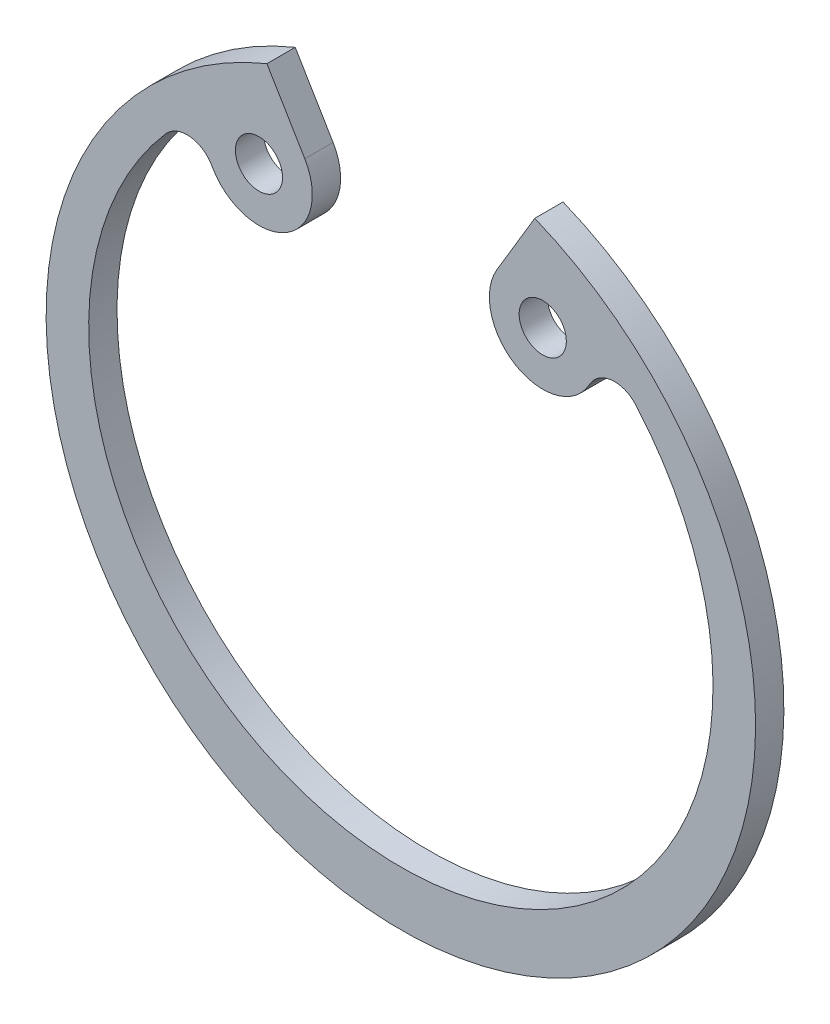
SolidWorks part; units mm, degrees
material "S890"
ref_plane "Front Plane" through (0, 0, 0) normal (0, 0, 1) x (1, 0, 0)
ref_plane "Top Plane" through (0, 0, 0) normal (0, 1, 0) x (1, 0, 0)
ref_plane "Right Plane" through (0, 0, 0) normal (1, 0, 0) x (0, 0, -1)
sketch "Sketch1" plane through (0, 0, 0) normal (0, 0, 1) x (1, 0, 0)
  line L0 (7.0978, 17.4087) -> (5.0915, 14.0476)
  line L1 (9.9485, 11.1484) -> (11.0285, 12.9577)
  line L2 (0, -18.8) -> (0, 6.7633) construction
  line L3 (0, 0) -> (7.52, 12.598) construction
  line L4 (-9.9485, 11.1484) -> (-5.0915, 14.0476) construction
  line L5 (9.9485, 11.1484) -> (5.0915, 14.0476) construction
  line L6 (0, 0) -> (-7.52, 12.598) construction
  line L7 (-9.9485, 11.1484) -> (-11.0285, 12.9577)
  line L8 (-7.0978, 17.4087) -> (-5.0915, 14.0476)
  arc A0 (-7.0978, 17.4087) -> (7.0978, 17.4087) centre (0, 0) ccw
  circle A1 centre (-7.52, 12.598) radius 1.25
  arc A2 (5.0915, 14.0476) -> (9.9485, 11.1484) centre (7.52, 12.598) ccw
  arc A3 (-11.0285, 12.9577) -> (11.0285, 12.9577) centre (0, 0.6258) ccw
  arc A4 (-5.0915, 14.0476) -> (-9.9485, 11.1484) centre (-7.52, 12.598) cw
  circle A5 centre (0, 0) radius 18.8 construction
  circle A6 centre (0, 0.6258) radius 16.544 construction
  circle A8 centre (7.52, 12.598) radius 1.25
  arc A10 (7.52, 12.598) -> (-7.52, 12.598) centre (0, 0) ccw construction
  point P16 (0, 18.8)
  point P18 (0, 17.1698)
  dimension "Dmin" = 37.6
  dimension "r_d1" = 2.8283
  dimension "d1" = 2.5
  dimension "r_holes" = 14.6717
  dimension "D_in" = 33.088
  dimension "e" = 1.6302
  dimension "G" = 7.52
extrude "Boss-Extrude1" add sketch "Sketch1" along normal mid plane 1.5
fillet "Fillet1" radius 1.5 2 edges at (11.0285, 12.9577, 0) (-11.0285, 12.9577, 0)
